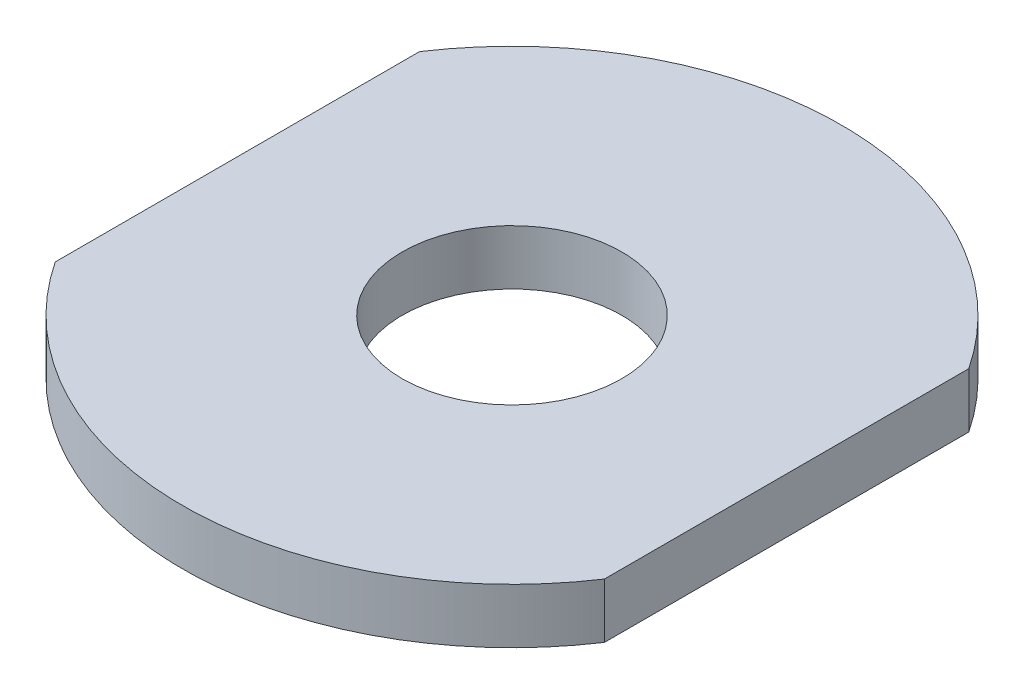
SolidWorks part; units mm, degrees
ref_plane "Front Plane" through (0, 0, 0) normal (0, 0, 1) x (1, 0, 0)
ref_plane "Top Plane" through (0, 0, 0) normal (0, 1, 0) x (1, 0, 0)
ref_plane "Right Plane" through (0, 0, 0) normal (1, 0, 0) x (0, 0, -1)
sketch "Sketch1" plane through (0, 0, 0) normal (0, 1, 0) x (1, 0, 0)
  circle A0 centre (0, 0) radius 2
  circle A1 centre (0, 0) radius 6
  dimension "D1" = 12
  dimension "D2" = 4
extrude "Boss-Extrude1" add sketch "Sketch1" along normal blind 1
sketch "Sketch2" plane through (0, 1, 0) normal (0, 1, 0) x (1, 0, 0)
  line L0 (-5, -3.3166) -> (-5, 3.3166)
  line L1 (5, 3.3166) -> (5, -3.3166)
  circle A0 centre (0, 0) radius 6 construction
  arc A1 (-5, 3.3166) -> (-5, -3.3166) centre (0, 0) ccw
  arc A2 (5, -3.3166) -> (5, 3.3166) centre (0, 0) ccw
  point P4 (4.6781, -3.757)
  dimension "D1" = 10
extrude "Cut-Extrude1" cut sketch "Sketch2" against normal through all
